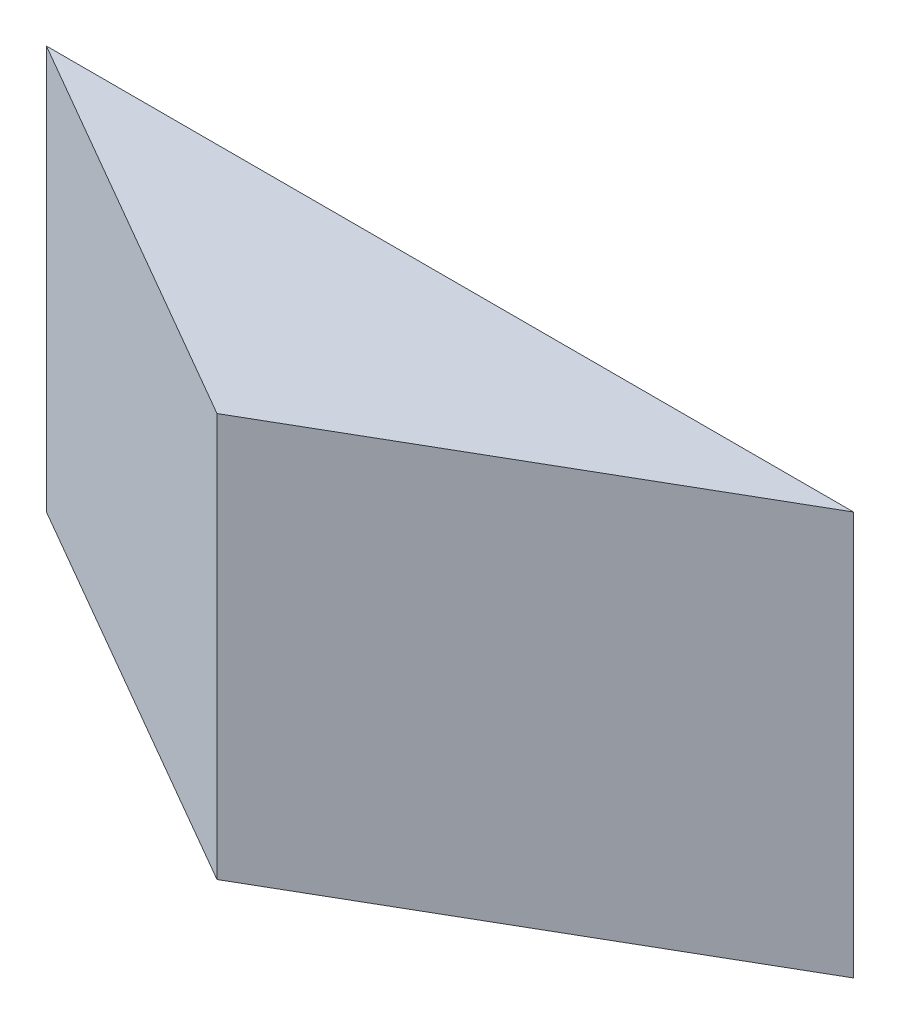
SolidWorks part; units mm, degrees
ref_plane "Přední rovina" through (0, 0, 0) normal (0, 0, 1) x (1, 0, 0)
ref_plane "Horní rovina" through (0, 0, 0) normal (0, 1, 0) x (1, 0, 0)
ref_plane "Pravá rovina" through (0, 0, 0) normal (1, 0, 0) x (0, 0, -1)
sketch "Sketch1" plane through (0, 0, 0) normal (0, 1, 0) x (1, 0, 0)
  line L0 (-20, 0) -> (20, 0)
  line L1 (20, 0) -> (0, -11.547)
  line L2 (0, -11.547) -> (0, 0) construction
  line L3 (-20, 0) -> (0, -11.547)
  dimension "D1" = 30
  dimension "D2" = 20
extrude "Boss-Extrude1" add sketch "Sketch1" along normal blind 20
